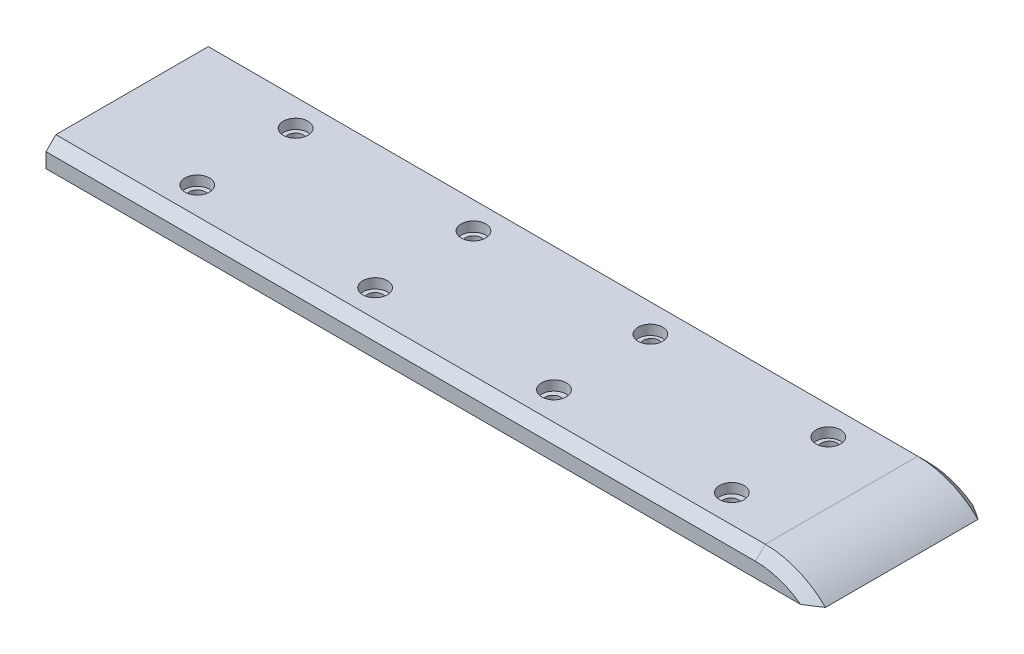
SolidWorks part; units mm, degrees
ref_plane "Front Plane" through (0, 0, 0) normal (0, 0, 1) x (1, 0, 0)
ref_plane "Top Plane" through (0, 0, 0) normal (0, 1, 0) x (1, 0, 0)
ref_plane "Right Plane" through (0, 0, 0) normal (1, 0, 0) x (0, 0, -1)
sketch "Sketch1" plane through (0, 0, 0) normal (0, 0, 1) x (1, 0, 0)
  line L0 (-75, 0) -> (75, 0) construction
  line L4 (-75, 17.5) -> (75, 17.5)
  line L6 (87.2474, 12.5) -> (-87.2474, 12.5)
  arc A2 (-75, 17.5) -> (-87.2474, 12.5) centre (-75, 0) ccw
  arc A3 (87.2474, 12.5) -> (75, 17.5) centre (75, 0) ccw
  point P2 (0, 0)
  point P5 (0, 0)
  dimension "D1" = 17.5
  dimension "D2" = 150
  dimension "D3" = 5
extrude "Boss-Extrude1" add sketch "Sketch1" along normal mid plane 35
sketch "Sketch2" plane through (0, 0, 0) normal (0, 0, 1) x (1, 0, 0)
  line L0 (75, 17.5) -> (-75, 17.5) construction
  line L1 (-87.2474, 12.5) -> (-69.2474, 12.5)
  line L2 (-87.2474, 12.5) -> (-87.2474, 17.5)
  line L3 (-87.2474, 17.5) -> (-69.2474, 17.5)
  line L4 (-69.2474, 12.5) -> (-69.2474, 17.5)
  dimension "D1" = 18
extrude "Cut-Extrude1" cut sketch "Sketch2" against normal mid plane 35
sketch "Sketch3" plane through (0, 12.5, 0) normal (0, -1, 0) x (1, 0, 0)
  line L0 (-69.2474, -17.5) -> (-69.2474, 17.5) construction
  line L1 (-69.2474, -17.5) -> (87.2474, -17.5) construction
  circle A0 centre (-46, -10) radius 1.625
  circle A1 centre (-9.8333, -10) radius 1.625
  circle A2 centre (26.3333, -10) radius 1.625
  circle A3 centre (62.5, -10) radius 1.625
  dimension "D1" = 3.25
  dimension "D2" = 36.1667
  dimension "D3" = 36.1667
  dimension "D4" = 36.1667
  dimension "D5" = 23.2474
  dimension "D6" = 7.5
extrude "Cut-Extrude2" cut sketch "Sketch3" against normal up to surface (5 mm away) up to face at (2.8763, 17.5, 0)
sketch "Sketch4" plane through (0, 17.5, 0) normal (0, 1, 0) x (1, 0, 0)
  circle A0 centre (62.5, 9.8) radius 2.5
  circle A1 centre (26.3333, 9.8) radius 2.5
  circle A2 centre (-9.8333, 10) radius 2.5
  circle A3 centre (-46, 10) radius 2.5
  dimension "D1" = 5
extrude "Cut-Extrude3" cut sketch "Sketch4" against normal blind 2
mirror "Mirror1" about plane through (0, 0, 0) normal (0, 0, 1) of "Cut-Extrude3", "Cut-Extrude2"
chamfer "Chamfer1" distance 2 angle 45 4 edges at (81.6144, 16.2019, 17.5) (2.8763, 17.5, 17.5) (81.6144, 16.2019, -17.5) (2.8763, 17.5, -17.5)
